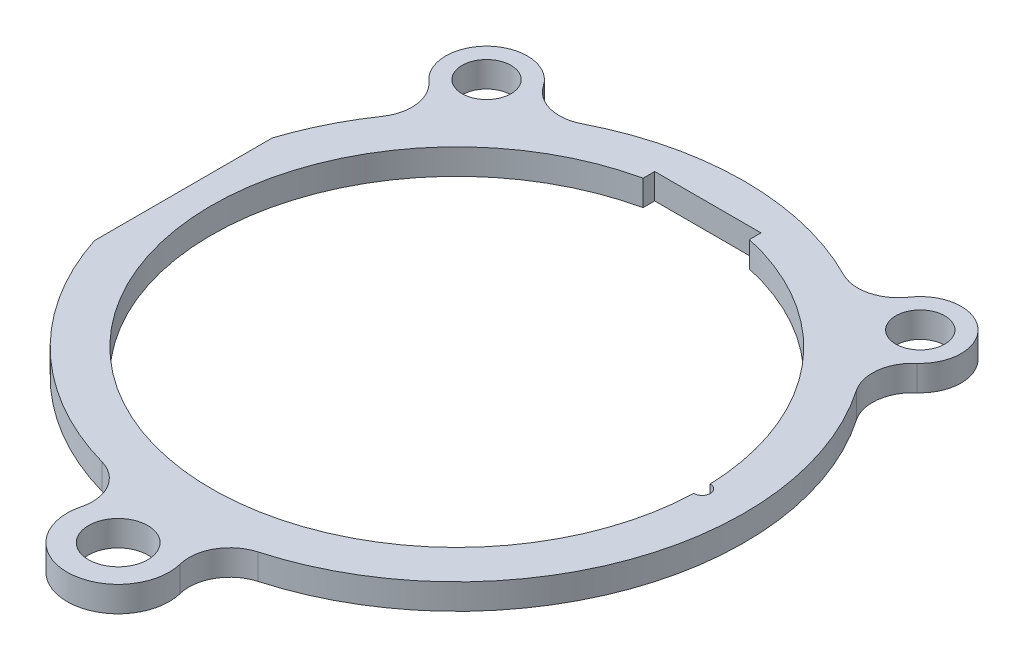
SolidWorks part; units mm, degrees
ref_plane "Front" through (0, 0, 0) normal (0, 0, 1) x (1, 0, 0)
ref_plane "Top" through (0, 0, 0) normal (0, 1, 0) x (1, 0, 0)
ref_plane "Right" through (0, 0, 0) normal (1, 0, 0) x (0, 0, -1)
sketch "Sketch1" plane through (0, 0, 0) normal (0, 1, 0) x (1, 0, 0)
  line L0 (0, -15.24) -> (0, 15.5956) construction
  line L1 (-3.302, 15.5956) -> (3.302, 15.5956)
  line L2 (-3.302, 15.5956) -> (-3.302, 14.878)
  line L3 (3.302, 15.5956) -> (3.302, 14.878)
  circle A0 centre (0, 0) radius 15.24
  circle A1 centre (0, 0) radius 21.59
  dimension "D1" = 30.48
  dimension "D3" = 30.8356
  dimension "D4" = 6.604
  dimension "D2" = 6.35
extrude "Boss-Extrude1" add sketch "Sketch1" along normal mid plane 1.5875 contours A1 A0 L2 L1 L3
sketch "Sketch2" plane through (0, 0.7937, 0) normal (0, 1, 0) x (1, 0, 0)
  line L0 (0, 18.415) -> (0, -18.415) construction
  line L1 (0, -15.24) -> (0, -21.59) construction
  circle A0 centre (0, 18.415) radius 1.4224
  circle A1 centre (0, -18.415) radius 1.4224
  arc A2 (-3.302, 14.878) -> (3.302, 14.878) centre (0, 0) ccw construction
  circle A3 centre (0, 0) radius 21.59 construction
  dimension "D1" = 2.8448
extrude "Cut-Extrude1" cut sketch "Sketch2" against normal through all
sketch "Sketch3" plane through (0, 0.7937, 0) normal (0, 1, 0) x (1, 0, 0)
  line L0 (-20.8712, 5.5245) -> (-16.9841, 5.5245)
  line L1 (-16.9841, 5.5245) -> (-16.9841, -5.5245)
  line L2 (-16.9841, -5.5245) -> (-20.8712, -5.5245)
  line L3 (-16.9841, -5.5245) -> (-20.8712, -5.5245) construction
  line L4 (-20.8712, 5.5245) -> (-16.9841, 5.5245) construction
  circle A0 centre (0, 0) radius 21.59 construction
  arc A1 (-20.8712, 5.5245) -> (-20.8712, -5.5245) centre (0, 0) ccw
extrude "Cut-Extrude2" cut sketch "Sketch3" against normal through all
sketch "Sketch4" plane through (0, 0.7937, 0) normal (0, 1, 0) x (1, 0, 0)
  line L0 (15.748, 0) -> (-15.24, 0) construction
  circle A0 centre (15.24, 0) radius 0.508
  arc A1 (-3.302, 14.878) -> (3.302, 14.878) centre (0, 0) ccw construction
  dimension "D1" = 30.988
extrude "Cut-Extrude3" cut sketch "Sketch4" against normal through all
sketch "Sketch5" plane through (0, 0.7937, 0) normal (0, 1, 0) x (1, 0, 0)
  line L0 (-12.3201, -16.1591) -> (12.3201, 16.1591) construction
  line L1 (-13.8351, -15.0041) -> (10.8052, 17.3141)
  line L2 (-10.8052, -17.3141) -> (13.8351, 15.0041)
  line L3 (16.1591, -12.3201) -> (-16.1591, 12.3201) construction
  line L4 (15.0041, -13.8351) -> (-17.3141, 10.8052)
  line L5 (17.3141, -10.8052) -> (-15.0041, 13.8351)
  line L6 (0, 0) -> (2.7145, -20.1379) construction
  line L7 (1.8879, 0.2545) -> (4.6025, -19.8834)
  line L8 (-1.8879, -0.2545) -> (0.8266, -20.3924)
  line L9 (-16.1591, 12.3201) -> (12.3201, 16.1591) construction
  circle A0 centre (0, 0) radius 17.86
  arc A1 (-13.8351, -15.0041) -> (-10.8052, -17.3141) centre (-12.3201, -16.1591) ccw
  arc A2 (13.8351, 15.0041) -> (10.8052, 17.3141) centre (12.3201, 16.1591) ccw
  circle A3 centre (12.3201, 16.1591) radius 1.0922
  circle A4 centre (-12.3201, -16.1591) radius 1.0922
  arc A5 (15.0041, -13.8351) -> (17.3141, -10.8052) centre (16.1591, -12.3201) ccw
  arc A6 (-15.0041, 13.8351) -> (-17.3141, 10.8052) centre (-16.1591, 12.3201) ccw
  circle A7 centre (-16.1591, 12.3201) radius 1.0922
  circle A8 centre (16.1591, -12.3201) radius 1.0922
  arc A9 (1.8879, 0.2545) -> (-1.8879, -0.2545) centre (0, 0) ccw
  arc A10 (0.8266, -20.3924) -> (4.6025, -19.8834) centre (2.7145, -20.1379) ccw
  circle A11 centre (2.7145, -20.1379) radius 1.0922
  arc A12 (16.1591, -12.3201) -> (2.7145, -20.1379) centre (0, 0) cw construction
  point P6 (0, 0)
  point P17 (0, 0)
  point P26 (1.3573, -10.0689)
  line M7 (-20.8712, 5.5245) -> (-16.9841, 5.5245)
  line M9 (-16.9841, -5.5245) -> (-20.8712, -5.5245)
  arc M10 (-20.8712, -5.5245) -> (-20.8712, 5.5245) centre (0, 0) ccw
  circle M11 centre (0, -18.415) radius 1.4224
  circle M12 centre (0, 18.415) radius 1.4224
  dimension "D2" = 3.81
  dimension "D1" = 3.81
extrude "Cut-Extrude4" cut sketch "Sketch5" against normal through all contours A6 A0 L4 M10 M7 | L5 A6 L4 A0 A7 M10 | A7 | A6 L5 A0 L1 A2 M12 M10 | A3 | L2 A2 L1 A0 A3 M10 | A5 A2 L2 A0 L5 M10 | A10 A5 L4 A0 L7 M10 | A5 L5 A0 L4 A8 M10 | A8 | A11 | A10 L7 A0 L8 A11 M10 M11 | A10 L8 A0 L2 A1 M11 M10 | A1 L1 A0 M9 M10 | A4 | A1 L2 A0 L1 A4 M10
sketch "Sketch6" plane through (0, 0.7937, 0) normal (0, 1, 0) x (1, 0, 0)
  line L0 (0, 17.86) -> (16.5405, 17.86) construction
  circle A0 centre (0, 0) radius 17.86
  circle A1 centre (13.4706, 15.32) radius 1.524
  circle A2 centre (-13.4706, 15.32) radius 1.524
  circle A3 centre (13.4706, 15.32) radius 2.54
  circle A4 centre (-13.4706, 15.32) radius 2.54
  circle A5 centre (9.2677, 18.1733) radius 2.54
  circle A6 centre (16.8382, 11.5166) radius 2.54
  circle A7 centre (-9.2677, 18.1733) radius 2.54
  circle A8 centre (-16.8382, 11.5166) radius 2.54
  circle A9 centre (0, -21.035) radius 1.8415
  circle A10 centre (0, -21.035) radius 3.175
  circle A11 centre (5.5404, -19.6332) radius 2.54
  circle A12 centre (-5.5404, -19.6332) radius 2.54
  arc M9 (-1.2889, -17.8134) -> (1.2889, -17.8134) centre (0, -18.415) cw
  arc M10 (1.2889, -17.8134) -> (1.2889, 17.8134) centre (0, 0) ccw
  arc M11 (1.2889, 17.8134) -> (-1.2889, 17.8134) centre (0, 18.415) cw
  dimension "D1" = 3.048
  dimension "D2" = 5.08
  dimension "D3" = 5.08
  dimension "D4" = 3.683
  dimension "D5" = 6.35
  dimension "D6" = 5.08
extrude "Boss-Extrude2" add sketch "Sketch6" against normal up to vertex contours A3 A1 | A6 A3 A0 | A5 A0 A3 | A7 A4 A0 | A4 A2 | A8 A0 A4 | A10 A9 | A11 A0 A10 M10 | A0 M9 | A12 A10 A0 | A0 M11
